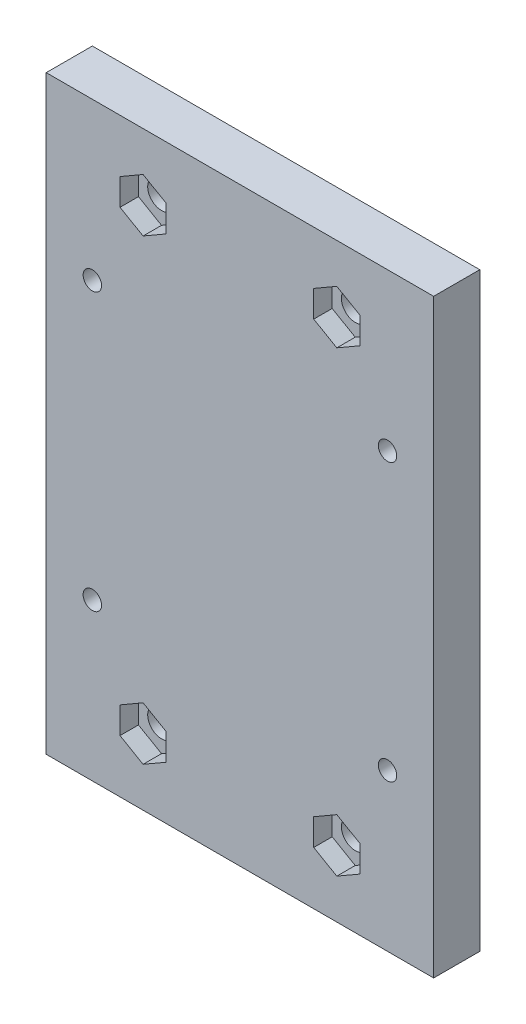
SolidWorks part; units mm, degrees
ref_plane "정면" through (0, 0, 0) normal (0, 0, 1) x (1, 0, 0)
ref_plane "윗면" through (0, 0, 0) normal (0, 1, 0) x (1, 0, 0)
ref_plane "우측면" through (0, 0, 0) normal (1, 0, 0) x (0, 0, -1)
sketch "스케치1" plane through (0, 0, 0) normal (0, 0, 1) x (1, 0, 0)
  line L1 (0, 0) -> (42, 0)
  line L2 (0, 0) -> (0, -64)
  line L3 (0, -64) -> (42, -64)
  line L4 (42, 0) -> (42, -64)
  dimension "D1" = 42
  dimension "D2" = 64
extrude "보스-돌출1" add sketch "스케치1" along normal blind 5
sketch "스케치2" plane through (0, 0, 5) normal (0, 0, 1) x (1, 0, 0)
  line L0 (34, -5.7566) -> (31.5, -4.3132)
  line L1 (13, -5.7566) -> (10.5, -4.3132)
  line L2 (10.5, -4.3132) -> (8, -5.7566)
  line L3 (8, -5.7566) -> (8, -8.6434)
  line L4 (8, -8.6434) -> (10.5, -10.0868)
  line L5 (10.5, -10.0868) -> (13, -8.6434)
  line L6 (13, -8.6434) -> (13, -5.7566)
  line L7 (0, 0) -> (0, -64) construction
  line L8 (31.5, -4.3132) -> (29, -5.7566)
  line L9 (42, 0) -> (0, 0) construction
  line L10 (10.5, -4.3132) -> (10.5, -10.0868)
  line L11 (21, 0) -> (21, -64)
  line L12 (0, -64) -> (42, -64) construction
  line L13 (42, -32) -> (0, -32)
  line L14 (42, -64) -> (42, 0) construction
  line L15 (29, -5.7566) -> (29, -8.6434)
  line L16 (29, -8.6434) -> (31.5, -10.0868)
  line L17 (31.5, -10.0868) -> (34, -8.6434)
  line L18 (34, -8.6434) -> (34, -5.7566)
  line L19 (31.5, -4.3132) -> (31.5, -10.0868)
  line L20 (34, -55.3566) -> (31.5, -53.9132)
  line L21 (31.5, -53.9132) -> (29, -55.3566)
  line L22 (29, -55.3566) -> (29, -58.2434)
  line L23 (29, -58.2434) -> (31.5, -59.6868)
  line L24 (31.5, -59.6868) -> (34, -58.2434)
  line L25 (34, -58.2434) -> (34, -55.3566)
  line L26 (31.5, -53.9132) -> (31.5, -59.6868)
  line L27 (13, -55.3566) -> (10.5, -53.9132)
  line L28 (10.5, -53.9132) -> (8, -55.3566)
  line L29 (8, -55.3566) -> (8, -58.2434)
  line L30 (8, -58.2434) -> (10.5, -59.6868)
  line L31 (10.5, -59.6868) -> (13, -58.2434)
  line L32 (13, -58.2434) -> (13, -55.3566)
  line L33 (10.5, -53.9132) -> (10.5, -59.6868)
  circle A0 centre (10.5, -7.2) radius 2.5 construction
  circle A1 centre (31.5, -7.2) radius 2.5 construction
  circle A2 centre (31.5, -56.8) radius 2.5 construction
  circle A3 centre (10.5, -56.8) radius 2.5 construction
  dimension "D7" = 2
  dimension "D1" = 5
  dimension "D2" = 10.5
  dimension "D3" = 7.2
  dimension "D4" = 5
  dimension "D5" = 7.2
  dimension "D6" = 10.5
  dimension "D8" = 7.2
extrude "컷-돌출1" cut sketch "스케치2" against normal blind 2 contours L10 L2 L3 L4 | L1 L10 L5 L6 | L19 L8 L15 L16 | L0 L19 L17 L18 | L33 L28 L29 L30 | L27 L33 L31 L32 | L26 L21 L22 L23 | L20 L26 L24 L25
sketch "스케치4" plane through (0, 0, 3) normal (0, 0, 1) x (1, 0, 0)
  line L0 (13, -8.6434) -> (13, -5.7566) construction
  line L1 (13, -58.2434) -> (13, -55.3566) construction
  circle A0 centre (10.5, -7.2) radius 1.5
  circle A1 centre (31.5, -7.2) radius 1.5
  circle A2 centre (31.5, -56.8) radius 1.5
  circle A3 centre (10.5, -56.8) radius 1.5
  point P12 (13, -7.2)
  point P19 (13, -56.8)
  dimension "D1" = 3
  dimension "D2" = 3
  dimension "D3" = 3
  dimension "D4" = 3
extrude "컷-돌출2" cut sketch "스케치4" against normal through all
sketch "스케치5" plane through (0, 0, 5) normal (0, 0, 1) x (1, 0, 0)
  line L1 (42, 0) -> (0, 0) construction
  line L2 (0, 0) -> (0, -64) construction
  circle A0 centre (5, -17) radius 1
  circle A1 centre (37, -17) radius 1
  circle A2 centre (5, -47) radius 1
  circle A3 centre (37, -47) radius 1
  point P10 (21, 0)
  point P13 (0, -32)
  point P14 (0, 0)
  point P15 (0, 0)
  dimension "D1" = 2
  dimension "D2" = 2
  dimension "D3" = 2
  dimension "D4" = 2
  dimension "D5" = 16
  dimension "D6" = 15
  dimension "D7" = 15
  dimension "D8" = 16
  dimension "D9" = 16
  dimension "D10" = 16
extrude "컷-돌출3" cut sketch "스케치5" against normal blind 5
